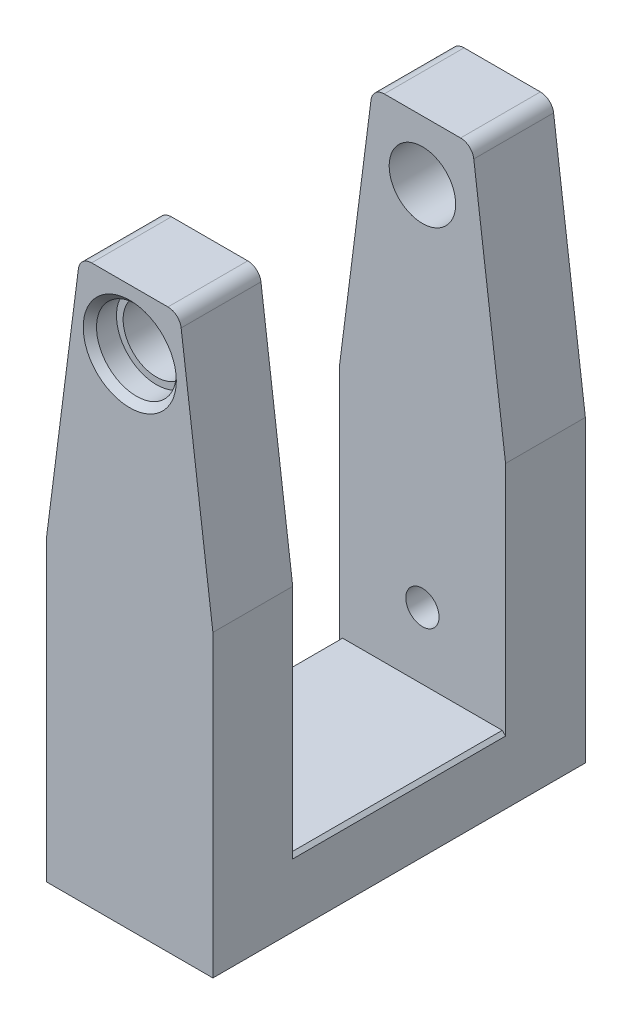
SolidWorks part; units mm, degrees
ref_plane "Front Plane" through (0, 0, 0) normal (0, 0, 1) x (1, 0, 0)
ref_plane "Top Plane" through (0, 0, 0) normal (0, 1, 0) x (1, 0, 0)
ref_plane "Right Plane" through (0, 0, 0) normal (1, 0, 0) x (0, 0, -1)
sketch "Sketch1" plane through (0, 0, 0) normal (0, 0, 1) x (1, 0, 0)
  line L0 (12.5, 0) -> (-12.5, 0)
  line L1 (0, 0) -> (0, 84) construction
  line L2 (7.5, 84) -> (-7.5, 84)
  line L3 (-12.5, 0) -> (-12.5, 45)
  line L4 (-7.5, 84) -> (-12.5, 45)
  line L5 (12.5, 0) -> (12.5, 45)
  line L6 (7.5, 84) -> (12.5, 45)
  point P4 (0, 0)
  point P9 (0, 84)
  dimension "D1" = 25
  dimension "D2" = 15
  dimension "D3" = 84
  dimension "D4" = 45
extrude "Boss-Extrude1" add sketch "Sketch1" along normal mid plane 56
sketch "Sketch2" plane through (12.5, 0, 0) normal (1, 0, 0) x (0, 0, -1)
  line L0 (-28, 84) -> (28, 84) construction
  line L1 (-16, 84) -> (16, 84)
  line L2 (-16, 84) -> (-16, 10)
  line L3 (-16, 10) -> (16, 10)
  line L4 (16, 84) -> (16, 10)
  line L5 (28, 45) -> (28, 84) construction
  line L6 (-28, 0) -> (28, 0) construction
  dimension "D1" = 12
  dimension "D2" = 32
  dimension "D3" = 10
extrude "Cut-Extrude1" cut sketch "Sketch2" against normal blind 56
hole_wizard "CBORE for M4 Hex Socket Head Cap Screw1" positions "Sketch3" profile "Sketch4" counterbore size "M4" standard "ISO"
sketch "Sketch3" plane through (0, 0, -28) normal (0, 0, -1) x (-1, 0, 0)
  line L0 (0, 84) -> (0, 75) construction
  line L1 (-7.5, 84) -> (7.5, 84) construction
  point P0 (0, 75)
  dimension "D1" = 9
sketch "Sketch4" plane through (0, 75, -28) normal (1, 0, 0) x (0, 1, 0)
  line L0 (0, 0) -> (0, 23.0043)
  line L1 (0, 23.0043) -> (5, 20)
  line L2 (5, 20) -> (5, 4)
  line L3 (5, 4) -> (6, 4)
  line L5 (6, 4) -> (6, 1)
  line L6 (6, 1) -> (7, 0)
  line L7 (7, 0) -> (0, 0)
  line L8 (-6, 1) -> (-7, 0) construction
  line L10 (0, 23.0043) -> (-5, 20) construction
  line L11 (0, -6.35) -> (0, 107.95) construction
  dimension "Hole Dia." = 10
  dimension "Hole Depth" = 20
  dimension "C'Bore Dia." = 12
  dimension "C'Bore Depth" = 4
  dimension "Near C'Sink Dia." = 14
  dimension "Near C'Sink Angle" = 90
  dimension "Drill Angle" = 118
mirror "Mirror1" about plane through (0, 0, 0) normal (0, 0, 1) of "CBORE for M4 Hex Socket Head Cap Screw1"
fillet "Fillet1" radius 2 4 edges at (7.5, 84, -22) (7.5, 84, 22) (-7.5, 84, 22) (-7.5, 84, -22)
chamfer "Chamfer1" distance 0.5 angle 45 2 edges at (-12.5, 10, 0) (12.5, 10, 0)
hole_wizard "M6 Tapped Hole2" positions "Sketch7" profile "Sketch8" tap size "M6" standard "ISO"
sketch "Sketch7" plane through (0, 0, -28) normal (0, 0, -1) x (-1, 0, 0)
  line L2 (0, 0) -> (0, 20) construction
  point P0 (0, 20)
  dimension "D1" = 20
sketch "Sketch8" plane through (0, 20, -28) normal (1, 0, 0) x (0, 1, 0)
  line L0 (0, 0) -> (0, 28.5022)
  line L1 (0, 28.5022) -> (2.5, 27)
  line L2 (2.5, 27) -> (2.5, 0.525)
  line L3 (2.5, 0.525) -> (3.025, 0)
  line L5 (3.025, 0) -> (0, 0)
  line L6 (-2.5, 0.525) -> (-3.025, 0) construction
  line L10 (0, 28.5022) -> (-2.5, 27) construction
  line L11 (0, -6.35) -> (0, 107.95) construction
  dimension "Tap Drill Dia." = 5
  dimension "Tap Drill Depth" = 27
  dimension "Near C'Sink Dia." = 6.05
  dimension "Near C'Sink Angle" = 90
  dimension "Drill Angle" = 118
cosmetic thread "Hole Thread2" parameters "D1"=12, "D2"=6
